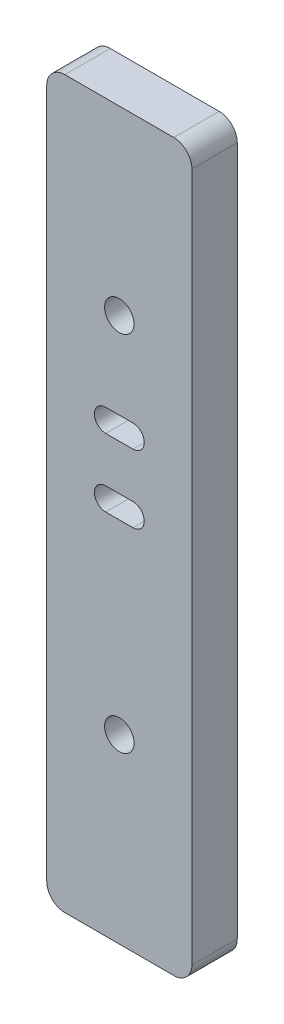
SolidWorks part; units mm, degrees
material "Maple"
ref_plane "Front Plane" through (0, 0, 0) normal (0, 0, 1) x (1, 0, 0)
ref_plane "Top Plane" through (0, 0, 0) normal (0, 1, 0) x (1, 0, 0)
ref_plane "Right Plane" through (0, 0, 0) normal (1, 0, 0) x (0, 0, -1)
sketch "Sketch1" plane through (0, 0, 0) normal (0, 0, 1) x (1, 0, 0)
  line L0 (8, 72) -> (8, 8) construction
  line L1 (0, 0) -> (16, 0)
  line L2 (0, 0) -> (0, 80)
  line L3 (0, 80) -> (16, 80)
  line L4 (16, 0) -> (16, 80)
  line L5 (8, 8) -> (8, 0) construction
  line L6 (6.5, 49.25) -> (9.5, 49.25) construction
  line L7 (6.5, 50.5) -> (9.5, 50.5)
  line L8 (6.5, 48) -> (9.5, 48)
  line L9 (6.5, 41.75) -> (9.5, 41.75) construction
  line L10 (6.5, 43) -> (9.5, 43)
  line L11 (6.5, 40.5) -> (9.5, 40.5)
  line L12 (16, 40) -> (8, 40) construction
  circle A0 centre (8, 72) radius 4 construction
  circle A1 centre (8, 8) radius 4 construction
  arc A2 (6.5, 50.5) -> (6.5, 48) centre (6.5, 49.25) ccw
  arc A3 (9.5, 48) -> (9.5, 50.5) centre (9.5, 49.25) ccw
  arc A4 (6.5, 43) -> (6.5, 40.5) centre (6.5, 41.75) ccw
  arc A5 (9.5, 40.5) -> (9.5, 43) centre (9.5, 41.75) ccw
  circle A6 centre (8, 20) radius 1.625
  circle A7 centre (8, 60) radius 1.625
  point P12 (8, 49.25)
  point P17 (8, 41.75)
  dimension "D2" = 8
  dimension "D10" = 3.25
  dimension "D1" = 8
  dimension "D3" = 64
  dimension "D4" = 8
  dimension "D5" = 8
  dimension "D6" = 8
  dimension "D7" = 3
  dimension "D8" = 2.5
  dimension "D9" = 5
  dimension "D11" = 12
  dimension "D12" = 12
extrude "Boss-Extrude1" add sketch "Sketch1" along normal blind 5
fillet "Fillet1" radius 2 4 edges at (0, 0, 2.5) (16, 0, 2.5) (16, 80, 2.5) (0, 80, 2.5)
